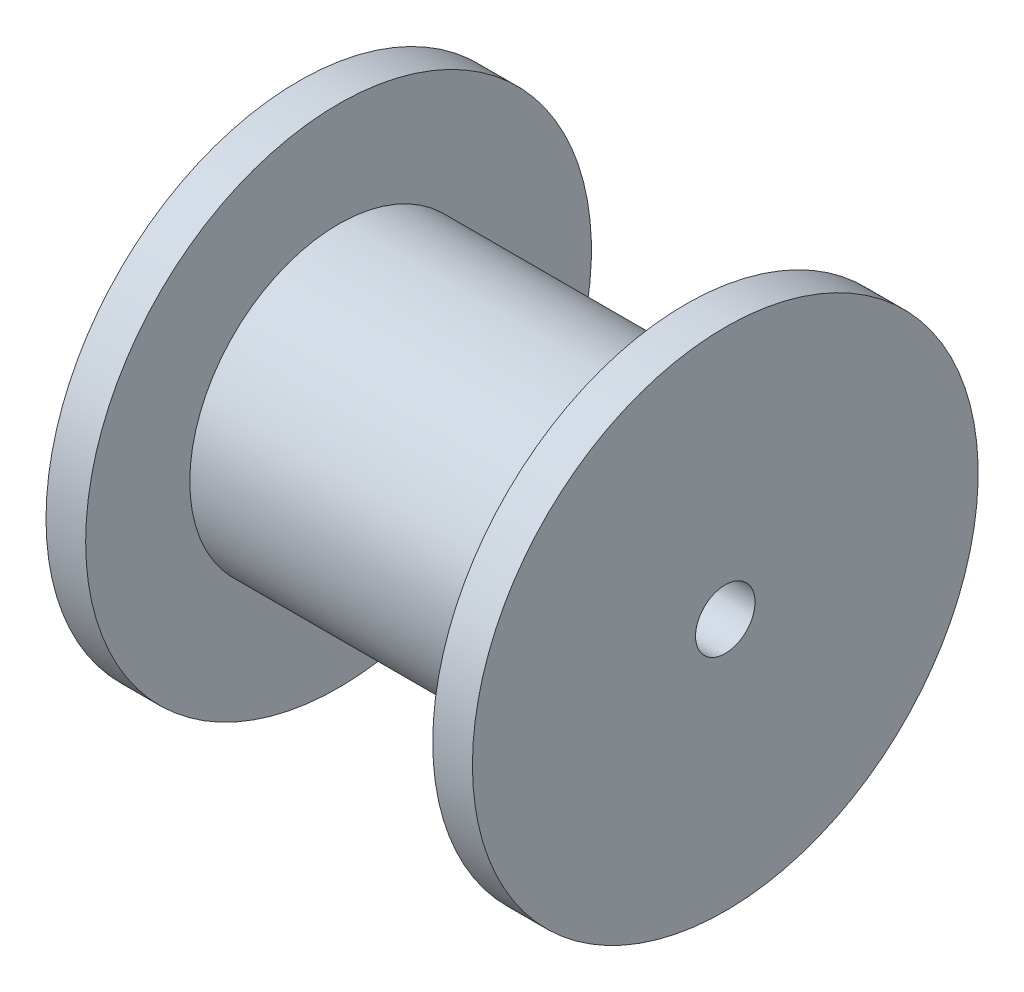
SolidWorks part; units mm, degrees
material "6061 Alloy"
ref_plane "Front Plane" through (0, 0, 0) normal (0, 0, 1) x (1, 0, 0)
ref_plane "Top Plane" through (0, 0, 0) normal (0, 1, 0) x (1, 0, 0)
ref_plane "Right Plane" through (0, 0, 0) normal (1, 0, 0) x (0, 0, -1)
sketch "Sketch1" plane through (0, 0, 0) normal (0, 0, 1) x (1, 0, 0)
  line L0 (0, 0) -> (0, 3)
  line L1 (0, 3) -> (0, 25.5)
  line L2 (0, 25.5) -> (4, 25.5)
  line L3 (4, 25.5) -> (4, 15)
  line L4 (4, 15) -> (39, 15)
  line L5 (39, 15) -> (39, 25.5)
  line L6 (39, 25.5) -> (43, 25.5)
  line L7 (43, 25.5) -> (43, 3)
  line L8 (43, 3) -> (43, 0)
  line L9 (0, 0) -> (43, 0) construction
  line L10 (0, 0) -> (43, 0)
  dimension "D1" = 10.5
  dimension "D2" = 10.5
  dimension "D3" = 43
  dimension "D4" = 3
  dimension "D5" = 3
  dimension "D6" = 12
  dimension "D7" = 4
  dimension "D8" = 4
  dimension "D9" = 35
revolve "Revolve1" add sketch "Sketch1" angle 360 about L10
sketch "Sketch8" plane through (0, 0, 0) normal (-1, 0, 0) x (0, 0, 1)
  circle A1 centre (0, 0) radius 3
  dimension "D1" = 6
extrude "Cut-Extrude1" cut sketch "Sketch8" against normal through all
